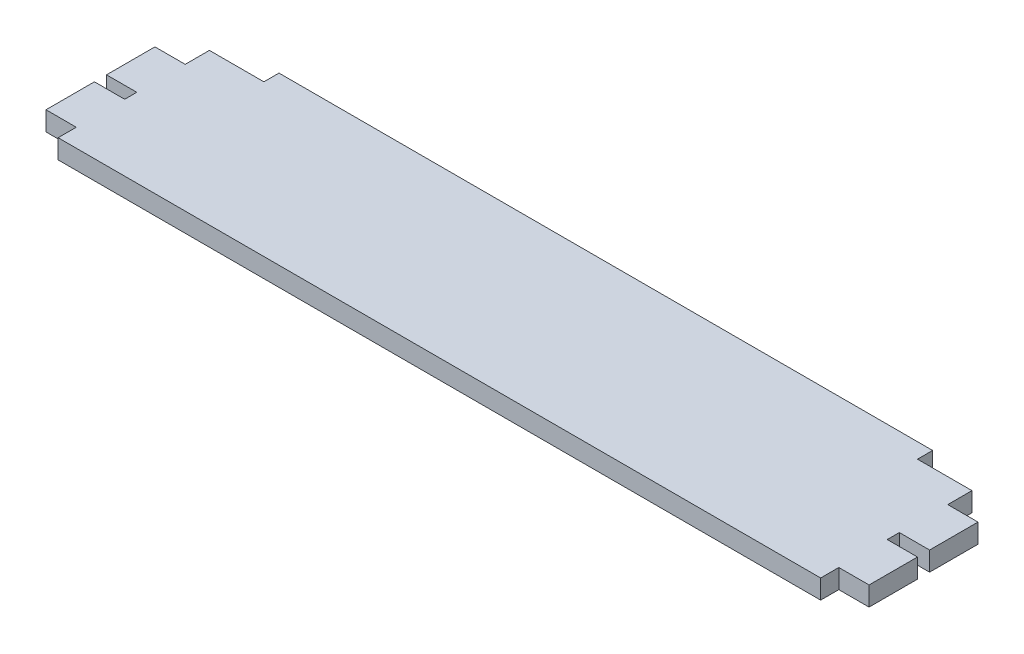
SolidWorks part; units mm, degrees
ref_plane "Front Plane" through (0, 0, 0) normal (0, 0, 1) x (1, 0, 0)
ref_plane "Top Plane" through (0, 0, 0) normal (0, 1, 0) x (1, 0, 0)
ref_plane "Right Plane" through (0, 0, 0) normal (1, 0, 0) x (0, 0, -1)
sketch "Sketch1" plane through (0, 0, 0) normal (0, 1, 0) x (1, 0, 0)
  line L1 (-63, -12) -> (63, -12)
  line L2 (-63, -12) -> (-63, 12)
  line L3 (-63, 12) -> (63, 12)
  line L4 (63, -12) -> (63, 12)
  line L5 (-63, -12) -> (63, 12) construction
  line L6 (-63, 12) -> (63, -12) construction
  line L7 (-63, 9) -> (-68, 9)
  line L8 (-63, 9) -> (-63, -9)
  line L9 (-63, -9) -> (-68, -9)
  line L10 (-68, 9) -> (-68, -9)
  line L11 (63, 9) -> (68, 9)
  line L12 (63, 9) -> (63, -9)
  line L13 (63, -9) -> (68, -9)
  line L14 (68, 9) -> (68, -9)
  line L15 (-6, -12) -> (6, -12)
  line L20 (-7, 12) -> (7, 12)
  line L21 (-63, 12) -> (63, 12)
  line L22 (-63, 12) -> (-63, 15.5)
  line L23 (-63, 15.5) -> (63, 15.5)
  line L24 (63, 12) -> (63, 15.5)
  point P0 (0, 0)
  dimension "D1" = 5
  dimension "D2" = 18
  dimension "D3" = 5
  dimension "D4" = 24
  dimension "D5" = 9
  dimension "D6" = 9
  dimension "D7" = 18
  dimension "D8" = 126
  dimension "D9" = 3.5
extrude "Boss-Extrude1" add sketch "Sketch1" along normal blind 3.175 contours L7 L10 L9 L2 | L1 L4 L3 L2 | L14 L11 L4 L13 | L22 L21 L24 L23
sketch "Sketch2" plane through (0, 3.175, 0) normal (0, 1, 0) x (1, 0, 0)
  line L1 (-63, 15.5) -> (-54, 15.5)
  line L2 (-63, 15.5) -> (-63, 13)
  line L3 (-63, 13) -> (-54, 13)
  line L4 (-54, 15.5) -> (-54, 13)
  line L5 (63, 15.5) -> (54, 15.5)
  line L6 (63, 15.5) -> (63, 13)
  line L7 (63, 13) -> (54, 13)
  line L8 (54, 15.5) -> (54, 13)
  dimension "D1" = 9
  dimension "D2" = 2.5
  dimension "D3" = 2.5
  dimension "D4" = 9
extrude "Cut-Extrude1" cut sketch "Sketch2" against normal through all
sketch "Sketch5" plane through (0, 3.175, 0) normal (0, 1, 0) x (1, 0, 0)
  line L0 (-68, 9) -> (-68, -9) construction
  line L1 (-68, 1) -> (-63, 1)
  line L2 (-68, 1) -> (-68, -1)
  line L3 (-68, -1) -> (-63, -1)
  line L4 (-63, 1) -> (-63, -1)
  line L5 (-63, -9) -> (-68, -9) construction
  line L6 (68, 9) -> (68, -9) construction
  line L7 (68, 1) -> (63, 1)
  line L8 (68, 1) -> (68, -1)
  line L9 (68, -1) -> (63, -1)
  line L10 (63, 1) -> (63, -1)
  line L11 (63, -9) -> (68, -9) construction
  dimension "D1" = 5
  dimension "D2" = 8
  dimension "2" = 2
  dimension "D3" = 5
  dimension "D4" = 2
  dimension "D5" = 8
extrude "Cut-Extrude2" cut sketch "Sketch5" against normal through all both contours L2 L1 L4 L3 | L8 L7 L10 L9
